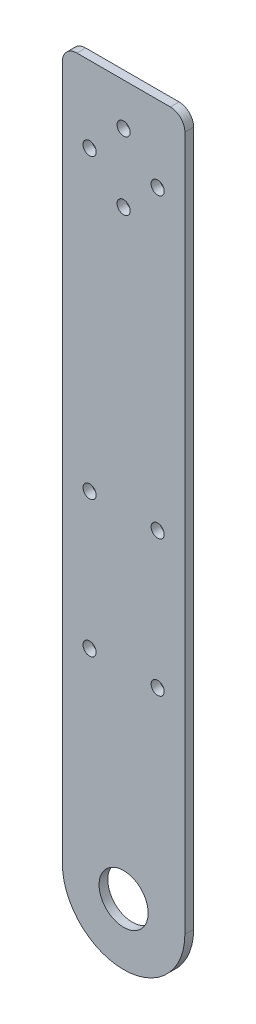
SolidWorks part; units mm, degrees
ref_plane "Plano frontal" through (0, 0, 0) normal (0, 0, 1) x (1, 0, 0)
ref_plane "Plano superior" through (0, 0, 0) normal (0, 1, 0) x (1, 0, 0)
ref_plane "Plano direito" through (0, 0, 0) normal (1, 0, 0) x (0, 0, -1)
sketch "Esboço1" plane through (0, 0, 0) normal (0, 0, 1) x (1, 0, 0)
  line L0 (-12.5962, 0) -> (-12.5962, 145.8324)
  line L1 (-12.5962, 145.8324) -> (12.5962, 145.8324)
  line L2 (12.5962, 145.8324) -> (12.5962, 0)
  line L3 (0, 145.8324) -> (0, -20.2118) construction
  line L4 (12.5962, 130.1858) -> (-12.5962, 130.1858) construction
  arc A0 (-12.5962, 0) -> (12.5962, 0) centre (0, 0) ccw
  circle A1 centre (7, 41.09) radius 1.35
  circle A2 centre (7, 69.09) radius 1.35
  circle A3 centre (-7, 41.09) radius 1.35
  circle A4 centre (-7, 69.09) radius 1.35
  circle A5 centre (7, 130.1858) radius 1.35
  circle A6 centre (0, 137.1858) radius 1.35
  circle A7 centre (-7, 130.1858) radius 1.35
  circle A8 centre (0, 123.1858) radius 1.35
  circle A9 centre (0, 0) radius 5.05
  dimension "D1" = 7
  dimension "D2" = 7
  dimension "D3" = 2.7
  dimension "D4" = 2.7
  dimension "D5" = 2.7
  dimension "D6" = 2.7
  dimension "D7" = 28
extrude "Ressalto-extrusão1" add sketch "Esboço1" along normal blind 1.8
fillet "Filete1" radius 3 1 edges at (-12.5962, 145.8324, 0.9)
fillet "Filete2" radius 3 1 edges at (12.5962, 145.8324, 0.9)
